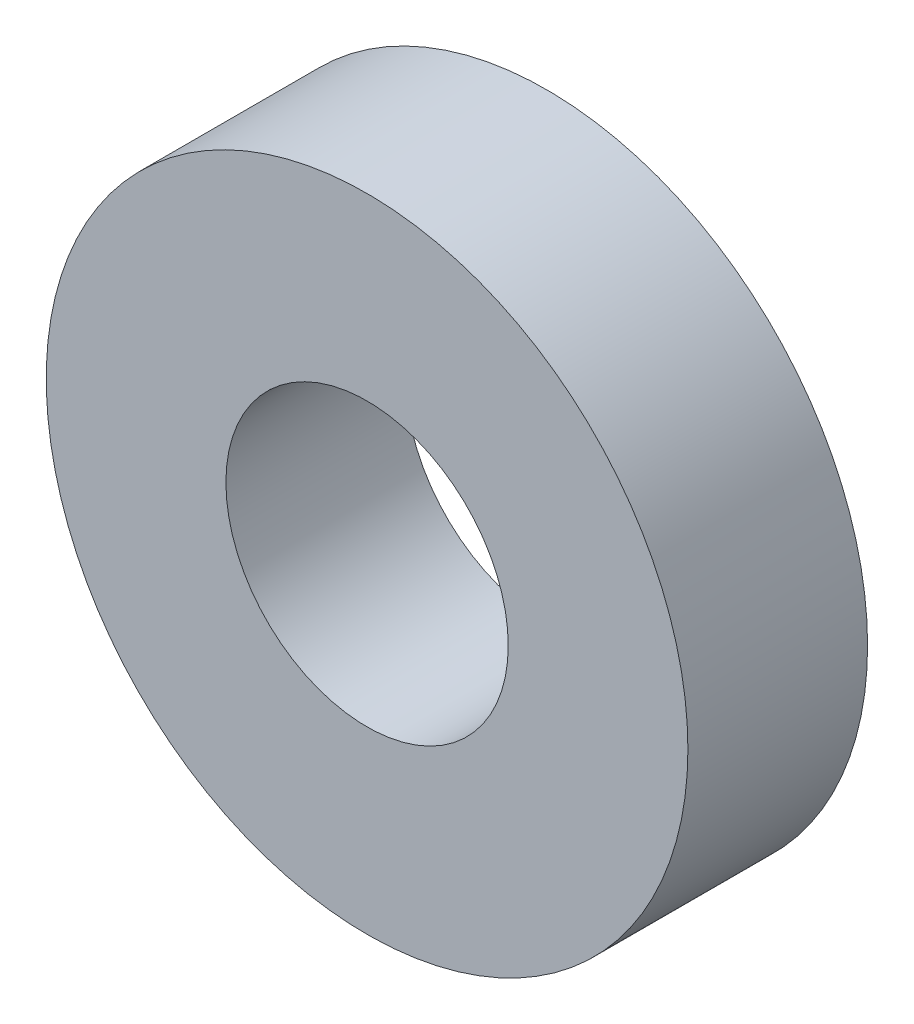
SolidWorks part; units mm, degrees
ref_plane "Front Plane" through (0, 0, 0) normal (0, 0, 1) x (1, 0, 0)
ref_plane "Top Plane" through (0, 0, 0) normal (0, 1, 0) x (1, 0, 0)
ref_plane "Right Plane" through (0, 0, 0) normal (1, 0, 0) x (0, 0, -1)
sketch "Sketch2" plane through (0, 0, 0) normal (0, 0, 1) x (1, 0, 0)
  circle A0 centre (0, 0) radius 25
  circle A1 centre (0, 0) radius 11
  dimension "D1" = 50
  dimension "D2" = 22
extrude "Boss-Extrude1" add sketch "Sketch2" along normal blind 14
